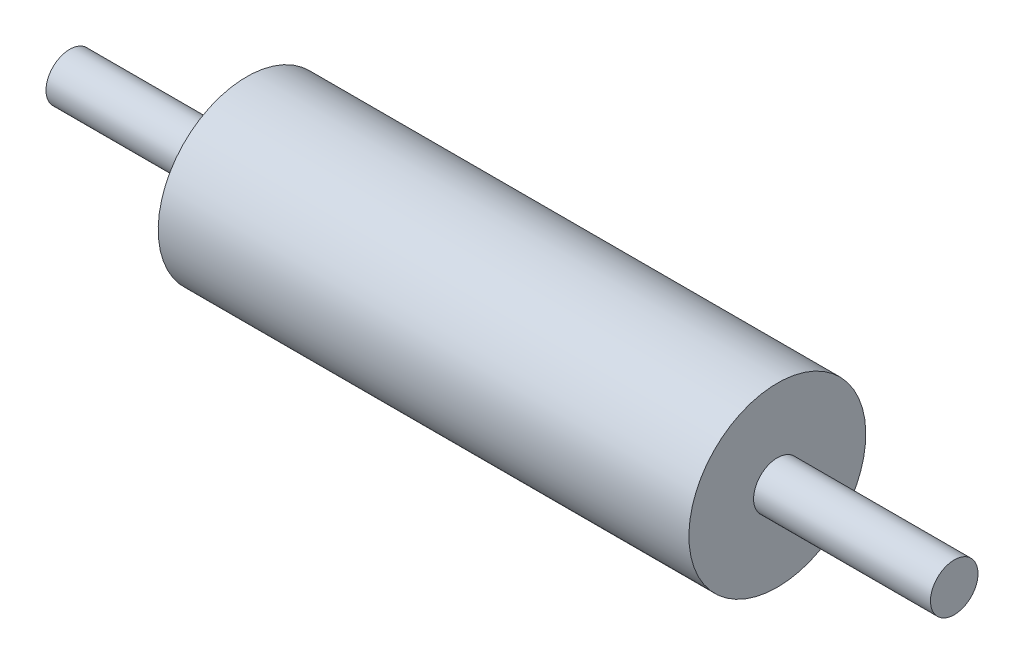
SolidWorks part; units mm, degrees
ref_plane "Front Plane" through (0, 0, 0) normal (0, 0, 1) x (1, 0, 0)
ref_plane "Top Plane" through (0, 0, 0) normal (0, 1, 0) x (1, 0, 0)
ref_plane "Right Plane" through (0, 0, 0) normal (1, 0, 0) x (0, 0, -1)
sketch "Sketch4" plane through (0, 0, 0) normal (0, 0, 1) x (1, 0, 0)
  line L0 (0, 0) -> (10, 0)
  line L1 (8, 0.2687) -> (8, 1)
  line L4 (8, 1) -> (2, 1)
  line L5 (2, 1) -> (2, 0.2687)
  line L8 (0, 0) -> (0, 0.2687)
  line L9 (0, 0.2687) -> (2, 0.2687)
  line L10 (8, 0.2687) -> (10, 0.2687)
  line L11 (10, 0.2687) -> (10, 0)
revolve "Revolve2" add sketch "Sketch4" angle 360 about L0
sketch "Sketch5" plane through (0, 0, 0) normal (-1, 0, 0) x (0, 0, 1)
  line L0 (0, 0.2687) -> (0, -0.2687)
  line L3 (0.2687, 0) -> (-0.2687, 0)
  circle A0 centre (0, 0) radius 0.2687 construction
  circle A1 centre (0, 0) radius 0.2687 construction
  circle A2 centre (0, 0) radius 0.2687
sketch "Sketch6" plane through (0, 0, 0) normal (0, 0, 1) x (1, 0, 0)
  line L0 (10, 0) -> (0, 0)
  line L1 (10, -0.2687) -> (10, 0.2687) construction
